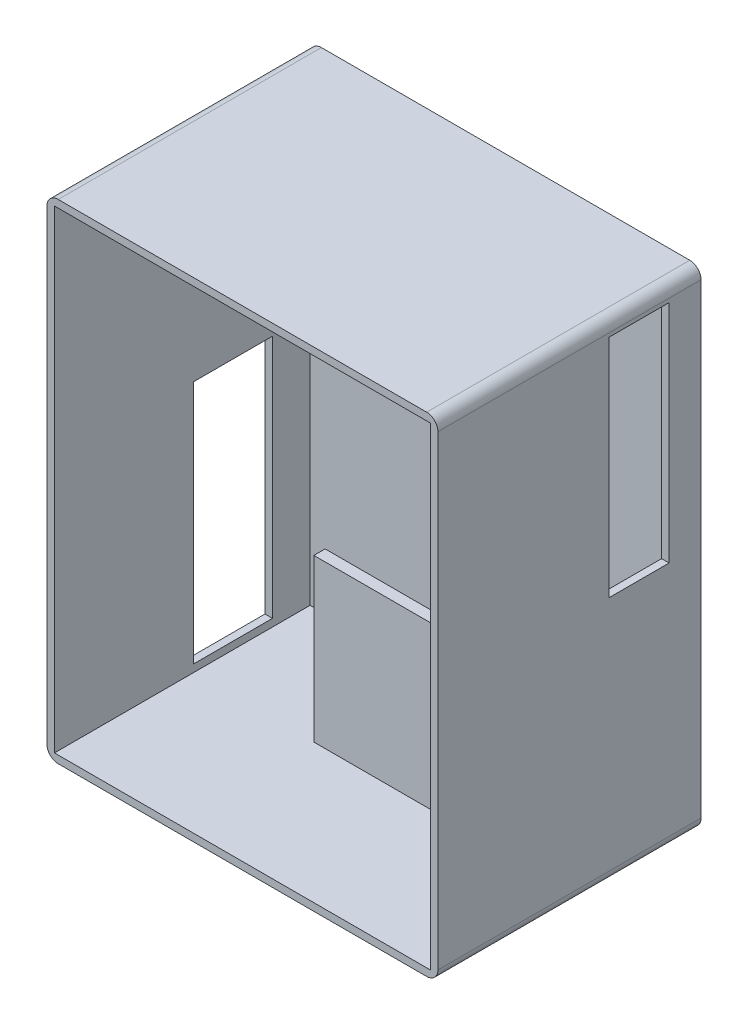
SolidWorks part; units mm, degrees
ref_plane "前基準面" through (0, 0, 0) normal (0, 0, 1) x (1, 0, 0)
ref_plane "上基準面" through (0, 0, 0) normal (0, 1, 0) x (1, 0, 0)
ref_plane "右基準面" through (0, 0, 0) normal (1, 0, 0) x (0, 0, -1)
sketch "草圖1" plane through (0, 0, 0) normal (0, 0, 1) x (1, 0, 0)
  line L1 (-52, 65) -> (52, 65)
  line L2 (-52, 65) -> (-52, -65)
  line L3 (-52, -65) -> (52, -65)
  line L4 (52, 65) -> (52, -65)
  line L5 (-52, 65) -> (52, -65) construction
  line L6 (-52, -65) -> (52, 65) construction
  point P0 (0, 0)
  dimension "D1" = 104
  dimension "D2" = 130
extrude "填料-伸長1" add sketch "草圖1" along normal blind 70
shell "薄殼1" thickness 2
sketch "草圖4" plane through (-52, 0, 0) normal (-1, 0, 0) x (0, 0, 1)
  line L0 (0, 65) -> (0, -65) construction
  line L1 (33, 4) -> (12, 4)
  line L2 (33, 4) -> (33, -61)
  line L3 (33, -61) -> (12, -61)
  line L4 (12, 4) -> (12, -61)
  line L5 (33, 4) -> (12, -61) construction
  line L6 (33, -61) -> (12, 4) construction
  line L7 (70, -65) -> (0, -65) construction
  point P0 (22.5, -28.5)
  dimension "D1" = 12
  dimension "D2" = 33
  dimension "D3" = 4
  dimension "D4" = 65
extrude "除料-伸長1" cut sketch "草圖4" against normal blind 70
sketch "草圖6" plane through (52, 0, 0) normal (1, 0, 0) x (0, 0, -1)
  line L0 (-70, 65) -> (0, 65) construction
  line L1 (-24.5, 1) -> (-8.5, 1)
  line L2 (-24.5, 1) -> (-24.5, 61)
  line L3 (-24.5, 61) -> (-8.5, 61)
  line L4 (-8.5, 1) -> (-8.5, 61)
  line L5 (-24.5, 1) -> (-8.5, 61) construction
  line L6 (-24.5, 61) -> (-8.5, 1) construction
  line L7 (0, -65) -> (0, 65) construction
  point P0 (-16.5, 31)
  dimension "D1" = 16
  dimension "D2" = 4
  dimension "D3" = 8.5
  dimension "D4" = 60
extrude "除料-伸長2" cut sketch "草圖6" against normal blind 70
sketch "草圖13" plane through (52, 0, 0) normal (1, 0, 0) x (0, 0, -1)
  line L0 (-12, 4) -> (-12, -61) construction
  line L1 (-33, -65) -> (-30, -65)
  line L2 (-33, -65) -> (-33, -20)
  line L3 (-33, -20) -> (-30, -20)
  line L4 (-30, -65) -> (-30, -20)
  line L5 (-33, -65) -> (-30, -20) construction
  line L6 (-33, -20) -> (-30, -65) construction
  line L13 (-70, -65) -> (0, -65) construction
  point P0 (-31.5, -42.5)
  dimension "D1" = 18
  dimension "D3" = 3
  dimension "D4" = 45
extrude "填料-伸長5" add sketch "草圖13" against normal blind 70
fillet "圓角2" radius 3 4 edges at (-52, -65, 35) (-52, 65, 35) (52, 65, 35) (52, -65, 35)
